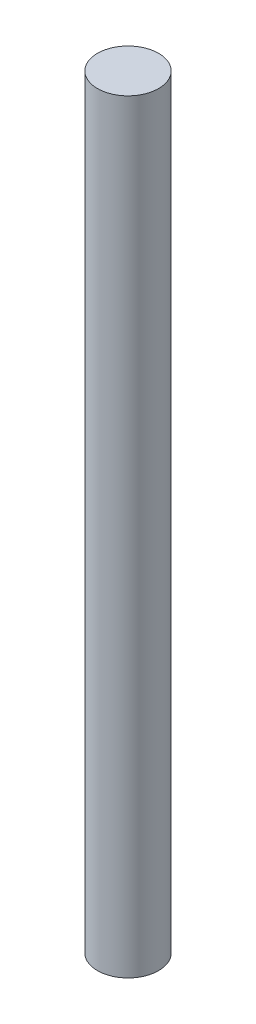
SolidWorks part; units mm, degrees
material "AISI 304"
ref_plane "Front Plane" through (0, 0, 0) normal (0, 0, 1) x (1, 0, 0)
ref_plane "Top Plane" through (0, 0, 0) normal (0, 1, 0) x (1, 0, 0)
ref_plane "Right Plane" through (0, 0, 0) normal (1, 0, 0) x (0, 0, -1)
sketch "Sketch2" plane through (0, 0, 0) normal (0, 0, 1) x (1, 0, 0)
  line L1 (0, 0) -> (-10, 0)
  line L2 (0, 0) -> (0, 250)
  line L3 (0, 250) -> (-10, 250)
  line L4 (-10, 0) -> (-10, 250)
  dimension "D1" = 250
  dimension "D2" = 10
revolve "Revolve1" add sketch "Sketch2" angle 360 about L2
